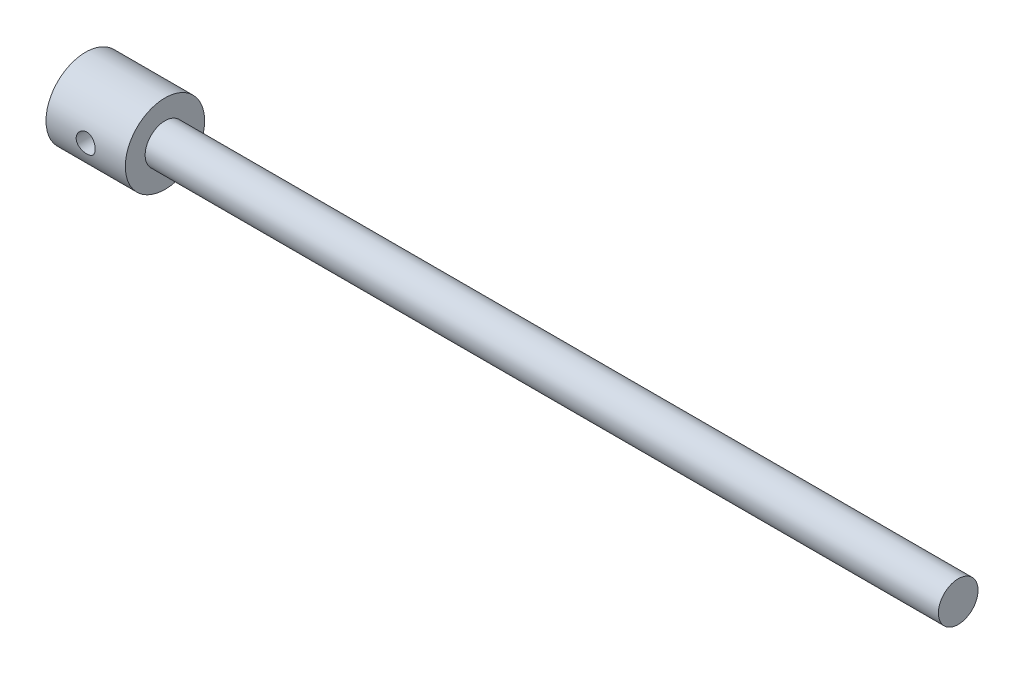
SolidWorks part; units mm, degrees
ref_plane "Front Plane" through (0, 0, 0) normal (0, 0, 1) x (1, 0, 0)
ref_plane "Top Plane" through (0, 0, 0) normal (0, 1, 0) x (1, 0, 0)
ref_plane "Right Plane" through (0, 0, 0) normal (1, 0, 0) x (0, 0, -1)
sketch "Sketch1" plane through (0, 0, 0) normal (0, 0, 1) x (1, 0, 0)
  line L0 (0, 0) -> (550, 0)
  line L1 (550, 0) -> (550, 12.5)
  line L2 (550, 12.5) -> (50, 12.5)
  line L3 (50, 12.5) -> (50, 25)
  line L4 (50, 25) -> (0, 25)
  line L5 (0, 25) -> (0, 0)
  dimension "D1" = 500
  dimension "D2" = 12.5
  dimension "D3" = 25
  dimension "D4" = 50
revolve "Revolve1" add sketch "Sketch1" angle 360 about L0
sketch "Sketch2" plane through (0, 0, 0) normal (0, 0, 1) x (1, 0, 0)
  circle A0 centre (25, 0) radius 6
  dimension "D1" = 12
  dimension "D2" = 25
extrude "Cut-Extrude1" cut sketch "Sketch2" against normal through all both and the other way through all
